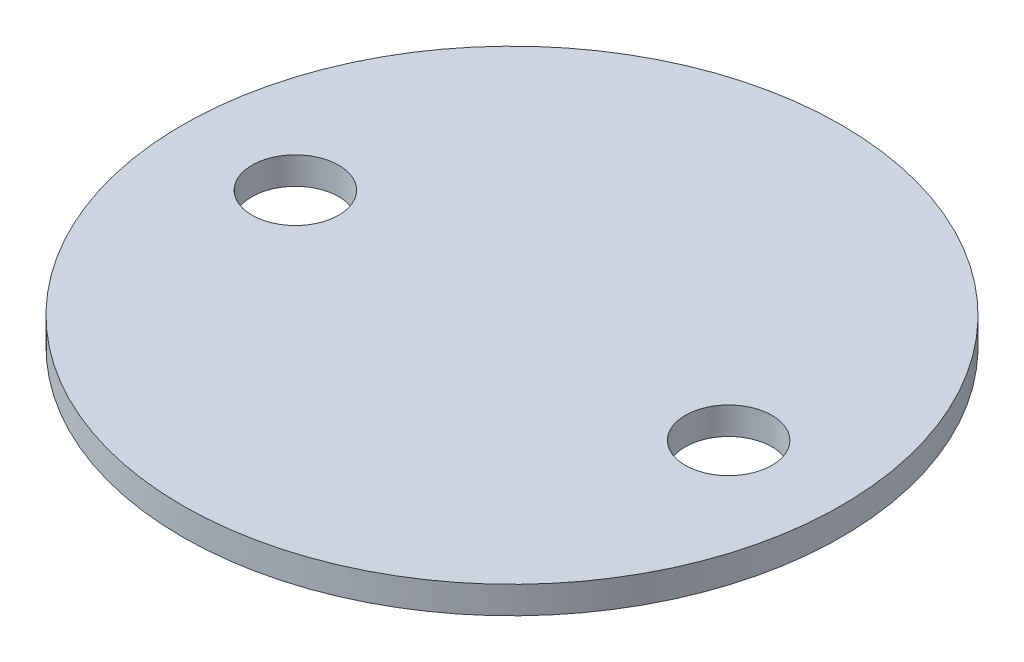
SolidWorks part; units mm, degrees
ref_plane "Front Plane" through (0, 0, 0) normal (0, 0, 1) x (1, 0, 0)
ref_plane "Top Plane" through (0, 0, 0) normal (0, 1, 0) x (1, 0, 0)
ref_plane "Right Plane" through (0, 0, 0) normal (1, 0, 0) x (0, 0, -1)
sketch "Sketch1" plane through (0, 0, 0) normal (0, 1, 0) x (1, 0, 0)
  line L0 (-35.547, 0) -> (35.1572, 0) construction
  line L1 (0, 34.6199) -> (0, -33.3517) construction
  circle A0 centre (0, 0) radius 24.15
  circle A1 centre (-15.875, 0) radius 3.175
  circle A2 centre (15.875, 0) radius 3.175
  dimension "D1" = 48.3
  dimension "D3" = 6.35
  dimension "D4" = 31.75
extrude "Boss-Extrude1" add sketch "Sketch1" along normal blind 2
